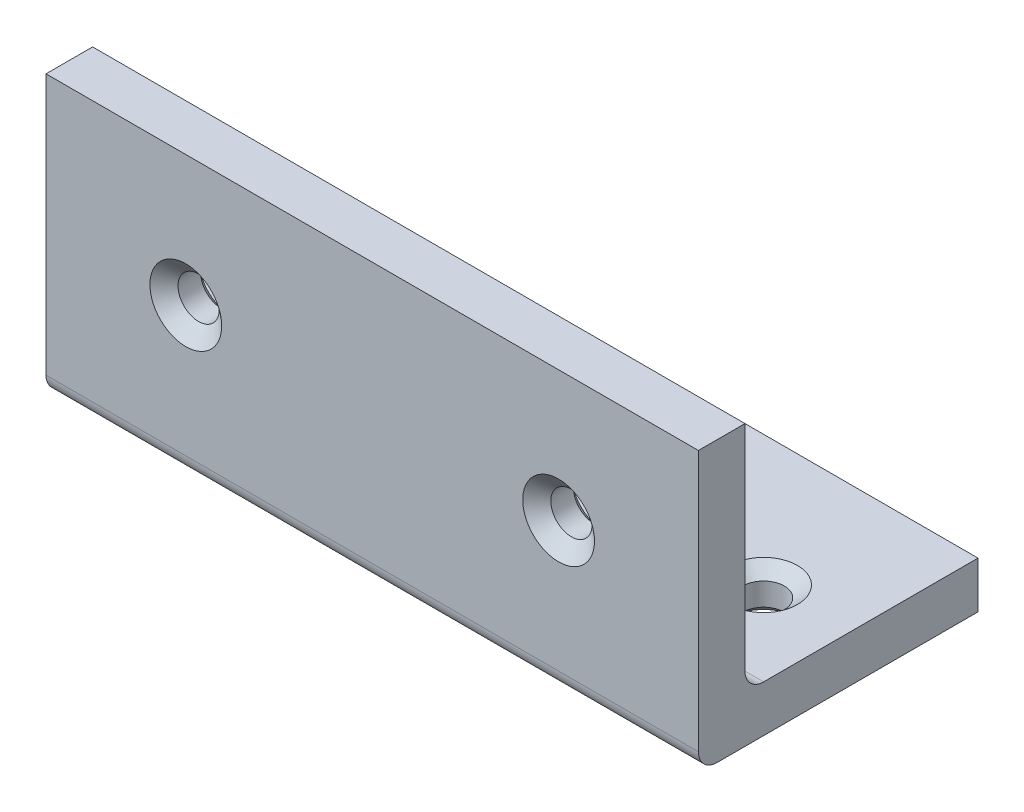
SolidWorks part; units mm, degrees
ref_plane "Front Plane" through (0, 0, 0) normal (0, 0, 1) x (1, 0, 0)
ref_plane "Top Plane" through (0, 0, 0) normal (0, 1, 0) x (1, 0, 0)
ref_plane "Right Plane" through (0, 0, 0) normal (1, 0, 0) x (0, 0, -1)
sketch "Sketch1" plane through (0, 0, 0) normal (0, 1, 0) x (1, 0, 0)
  line L0 (44.45, -19.05) -> (44.45, 19.05)
  line L1 (44.45, -19.05) -> (-44.45, -19.05)
  line L2 (44.45, 19.05) -> (-44.45, 19.05)
  line L3 (-44.45, -19.05) -> (-44.45, 19.05)
  line L4 (44.45, -19.05) -> (-44.45, 19.05) construction
  line L5 (44.45, 19.05) -> (-44.45, -19.05) construction
  point P1 (0, 0)
  dimension "D1" = 38.1
  dimension "D2" = 88.9
extrude "Boss-Extrude1" add sketch "Sketch1" along normal blind 6.35
sketch "Sketch2" plane through (0, 6.35, 0) normal (0, 1, 0) x (1, 0, 0)
  line L0 (44.45, -19.05) -> (44.45, 19.05) construction
  line L1 (-44.45, -19.05) -> (44.45, -19.05)
  line L2 (-44.45, -19.05) -> (-44.45, -12.7)
  line L3 (-44.45, -12.7) -> (44.45, -12.7)
  line L4 (44.45, -19.05) -> (44.45, -12.7)
  dimension "D1" = 6.35
extrude "Boss-Extrude2" add sketch "Sketch2" along normal blind 31.75
fillet "Fillet1" radius 2.54 1 edges at (0, 6.35, 12.7)
fillet "Fillet2" radius 2.54 1 edges at (0, 0, 19.05)
hole_wizard "CSK for #10 Flat Head Machine Screw (100)1" positions "3DSketch1" profile "Sketch3" countersink size "#10" standard "ANSI Inch" end condition through all
sketch3d "3DSketch1"
  line L0 (44.45, 38.1, 19.05) -> (44.45, 2.54, 19.05) construction
  line L1 (-44.45, 38.1, 19.05) -> (-44.45, 2.54, 19.05) construction
  line L2 (44.45, 38.1, 19.05) -> (44.45, 2.54, 19.05) construction
  line L3 (-44.45, 38.1, 19.05) -> (-44.45, 2.54, 19.05) construction
  line L4 (-44.45, 20.32, 19.05) -> (44.45, 20.32, 19.05) construction
  line L6 (44.45, 0, 16.51) -> (44.45, 0, -19.05) construction
  line L7 (-44.45, 0, -19.05) -> (-44.45, 0, 16.51) construction
  line L8 (44.45, 0, 16.51) -> (44.45, 0, -19.05) construction
  line L9 (-44.45, 0, -19.05) -> (-44.45, 0, 16.51) construction
  line L10 (-44.45, 0, -1.27) -> (44.45, 0, -1.27) construction
  point P0 (-25.4, 20.32, 19.05)
  point P2 (25.4, 20.32, 19.05)
  point P4 (33.02, 0, -1.27)
  point P6 (-33.02, 0, -1.27)
  point P45 (0, 6.35, -1.27)
  point P49 (-2.954, 6.35, -6.8038)
  point P50 (0, 0, -1.27)
  point P51 (0, 0, 0)
  dimension "D1" = 50.8
  dimension "D2" = 19.05
  dimension "D3" = 66.04
  dimension "D4" = 11.43
sketch "Sketch3" plane through (-25.4, 20.32, 19.05) normal (1, 0, 0) x (0, -1, 0)
  line L0 (0, 0) -> (0, 6.35)
  line L1 (0, 6.35) -> (4.6101, 6.35)
  line L2 (2.8067, 4.8368) -> (2.8067, 1.7477)
  line L3 (2.8067, 1.7477) -> (4.8895, 0)
  line L5 (4.8895, 0) -> (0, 0)
  line L6 (-2.8067, 1.7477) -> (-4.8895, 0) construction
  line L7 (4.6101, 6.35) -> (2.8067, 4.8368)
  line L8 (-4.6101, 6.35) -> (-2.8067, 4.8368) construction
  line L11 (0, -6.35) -> (0, 107.95) construction
  dimension "Thru Hole Dia." = 5.6134
  dimension "Thru Hole Depth" = 6.35
  dimension "Near C'Sink Dia." = 9.779
  dimension "Near C'Sink Angle" = 100
  dimension "Far C'Sink Dia." = 9.2202
  dimension "Far C'Sink Angle" = 100
